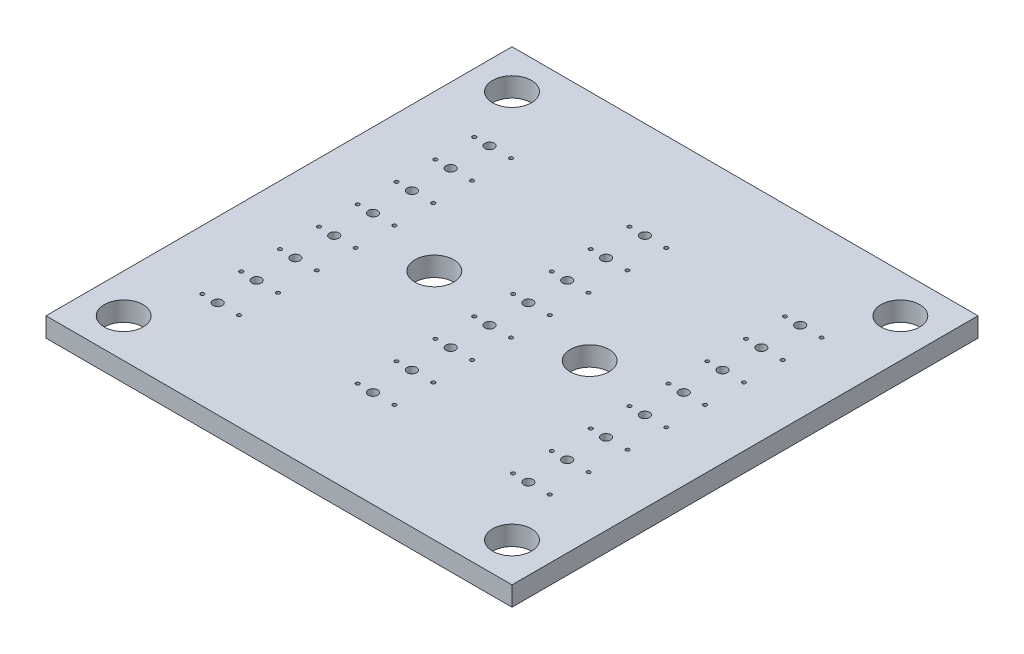
SolidWorks part; units mm, degrees
ref_plane "Front Plane" through (0, 0, 0) normal (0, 0, 1) x (1, 0, 0)
ref_plane "Top Plane" through (0, 0, 0) normal (0, 1, 0) x (1, 0, 0)
ref_plane "Right Plane" through (0, 0, 0) normal (1, 0, 0) x (0, 0, -1)
sketch "BaseWith Alignment" plane through (0, 0, 0) normal (0, 1, 0) x (1, 0, 0)
  line L0 (-6.35, 15.875) -> (-6.35, -60.325) construction
  line L1 (-12.7, 15.875) -> (63.5, 15.875)
  line L2 (-12.7, 15.875) -> (-12.7, -60.325)
  line L3 (-12.7, -60.325) -> (63.5, -60.325)
  line L4 (63.5, 15.875) -> (63.5, -60.325)
  line L5 (57.15, 15.875) -> (57.15, -60.325) construction
  line L6 (-6.35, 9.525) -> (57.15, 9.525) construction
  line L7 (-6.35, -53.975) -> (57.15, -53.975) construction
  line L8 (-12.7, -22.225) -> (63.5, -22.225) construction
  circle A0 centre (-6.35, 9.525) radius 3.175
  circle A1 centre (57.15, 9.525) radius 3.175
  circle A2 centre (-6.35, -53.975) radius 3.175
  circle A3 centre (57.15, -53.975) radius 3.175
  circle A4 centre (12.7, -22.225) radius 3.175
  circle A5 centre (38.1, -22.225) radius 3.175
  dimension "D3" = 6.35
  dimension "D1" = 76.2
  dimension "D2" = 76.2
  dimension "D4" = 6.35
  dimension "D5" = 6.35
  dimension "D6" = 6.35
  dimension "D7" = 6.35
  dimension "D8" = 25.4
  dimension "D9" = 25.4
  dimension "D10" = 12.7
  dimension "D11" = 9.525
extrude "Boss-Extrude1" add sketch "BaseWith Alignment" along normal blind 3.175
sketch "Sketch1" plane through (0, 0, 0) normal (0, -1, 0) x (-1, 0, 0)
  line L0 (-3, 0) -> (3, 0) construction
  line L1 (-3, 1.25) -> (3, 1.25) construction
  line L2 (-3, -1.25) -> (3, -1.25) construction
  line L22 (0.5, 0) -> (0.3393, 1.2396) construction
  line L23 (2.0179, 1.9614) -> (2.0179, -1.9614) construction
  line L25 (2.0179, -1.9614) -> (-3.1107, -1.2965) construction
  line L27 (2.0179, 1.9614) -> (-3.1107, 1.2965) construction
  line L28 (-3.1107, 1.2965) -> (-3.1107, -1.2965) construction
  line L29 (-3, 0) -> (-3.0386, 0.2975) construction
  line L30 (0.3393, 1.2396) -> (0.275, 1.7355) construction
  line L31 (-3.0386, 0.2975) -> (-3.1671, 1.2892) construction
  arc A0 (-3, 1.25) -> (-3, -1.25) centre (-3, 0) ccw construction
  arc A1 (3, -1.25) -> (3, 1.25) centre (3, 0) ccw construction
  circle A2 centre (0.5, 0) radius 0.762
  circle A3 centre (3, 0) radius 0.3
  circle A4 centre (-3, 0) radius 0.3
  arc A7 (-3.1, 0.2828) -> (-2.7, 0) centre (-3, 0) ccw construction
  circle A8 centre (0.5, 0) radius 1.25 construction
  circle A9 centre (0.5, 0) radius 1 construction
  arc A12 (2.0179, 1.9614) -> (2.0179, -1.9614) centre (2.2722, 0) cw construction
  arc A13 (-3.1107, 1.2965) -> (-3.1107, -1.2965) centre (-2.9426, 0) ccw construction
  point P2 (0, 0)
  point P25 (2.0179, 0)
  point P29 (-3.0543, 0)
  point P31 (-3.1107, 0)
  dimension "D3" = 0.6
  dimension "D5" = 1.524
  dimension "D6" = 0.6
  dimension "D7" = 2.5
  dimension "D8" = 2
  dimension "D2" = 2.5
  dimension "D4" = 2.5
  dimension "D1" = 3.5
  dimension "D10" = 3.9229
  dimension "D9" = 0.5
  dimension "D11" = 1
extrude "Cut-Extrude6" cut sketch "Sketch1" against normal through all
pattern_linear "LPattern1" count 8 spacing 6.35 along (0, 0, 1) count 3 spacing 25.4 along (1, 0, 0) of "Cut-Extrude6"
equation "\"StabilizerRodeHole\"=0.6"
equation "\"D3@Sketch1\"=\"StabilizerRodeHole\""
equation "\"D6@Sketch1\"=\"StabilizerRodeHole\""
